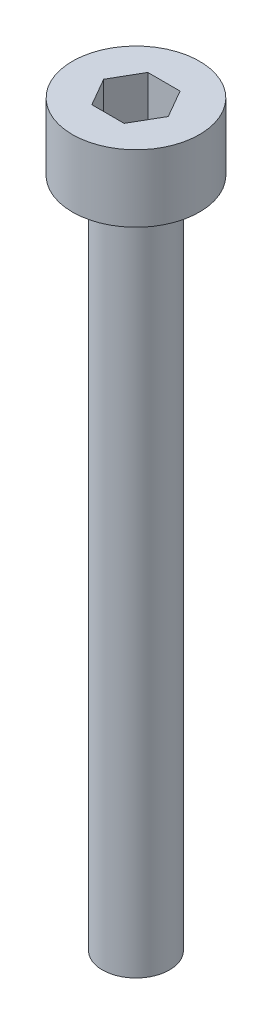
SolidWorks part; units mm, degrees
material "Plain Carbon Steel"
ref_plane "Front Plane" through (0, 0, 0) normal (0, 0, 1) x (1, 0, 0)
ref_plane "Top Plane" through (0, 0, 0) normal (0, 1, 0) x (1, 0, 0)
ref_plane "Right Plane" through (0, 0, 0) normal (1, 0, 0) x (0, 0, -1)
sketch "Sketch1" plane through (0, 0, 0) normal (0, 1, 0) x (1, 0, 0)
  line L1 (0.7217, 1.25) -> (-0.7217, 1.25)
  line L2 (-0.7217, 1.25) -> (-1.4434, 0)
  line L3 (-1.4434, 0) -> (-0.7217, -1.25)
  line L4 (-0.7217, -1.25) -> (0.7217, -1.25)
  line L5 (0.7217, -1.25) -> (1.4434, 0)
  line L6 (1.4434, 0) -> (0.7217, 1.25)
  circle A0 centre (0, 0) radius 1.25 construction
  circle A1 centre (0, 0) radius 2.84
  dimension "D1" = 5.68
  dimension "D2" = 2.5
extrude "Boss-Extrude1" add sketch "Sketch1" along normal blind 3
sketch "Sketch2" plane through (0, 0, 0) normal (0, -1, 0) x (1, 0, 0)
  circle A0 centre (0, 0) radius 1.5
  dimension "D1" = 3
extrude "Boss-Extrude2" add sketch "Sketch2" along normal blind 30
